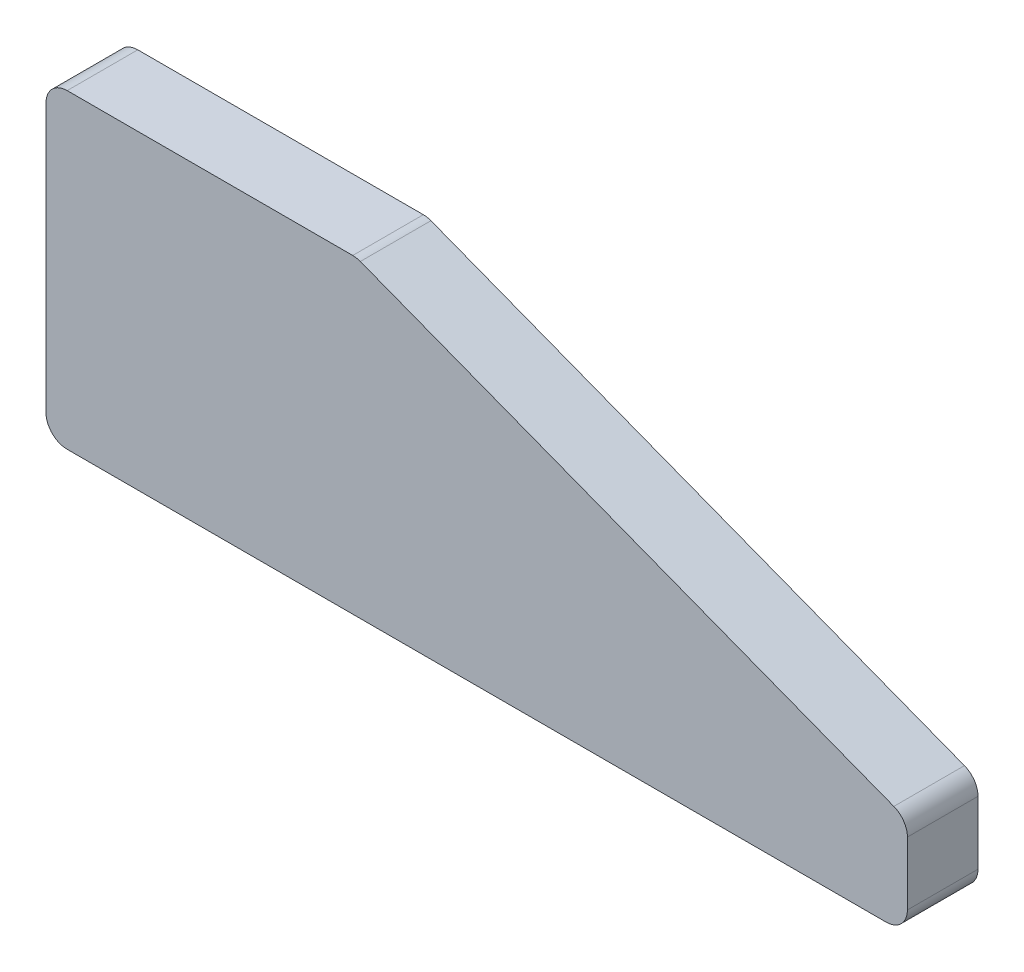
SolidWorks part; units mm, degrees
material "未指定"
ref_plane "正面" through (0, 0, 0) normal (0, 0, 1) x (1, 0, 0)
ref_plane "平面" through (0, 0, 0) normal (0, 1, 0) x (1, 0, 0)
ref_plane "右側面" through (0, 0, 0) normal (1, 0, 0) x (0, 0, -1)
sketch "ｽｹｯﾁ1" plane through (0, 0, 0) normal (0, 0, 1) x (1, 0, 0)
  line L0 (-22, -22) -> (100, -22)
  line L1 (100, -22) -> (100, -8)
  line L2 (100, -8) -> (22, 22)
  line L3 (22, 22) -> (-22, 22)
  line L4 (-22, 22) -> (-22, -22)
  line L5 (0, 0) -> (25, 0) construction
  dimension "D1" = 100
  dimension "D2" = 22
  dimension "D3" = 22
  dimension "D4" = 44
  dimension "D5" = 8
extrude "板 外形切り出し" add sketch "ｽｹｯﾁ1" along normal mid plane 10
fillet "角R" radius 3 5 edges at (-22, 22, 0) (22, 22, 0) (100, -8, 0) (100, -22, 0) (-22, -22, 0)
equation "\"JAW_LEN\" = 100"
equation "\"D1@ｽｹｯﾁ1\" = \"JAW_LEN\""
equation "\"JAW_HUB\" = 22"
equation "\"D2@ｽｹｯﾁ1\" = \"JAW_HUB\""
equation "\"D3@ｽｹｯﾁ1\" = \"JAW_HUB\""
equation "\"D4@ｽｹｯﾁ1\" = 2 * ( \"JAW_HUB\" )"
equation "\"JAW_TIP\" = 8"
equation "\"D5@ｽｹｯﾁ1\" = \"JAW_TIP\""
equation "\"PLATE_T\" = 10"
equation "\"D1@板 外形切り出し\" = \"PLATE_T\""
equation "\"JAW_R\" = 3"
equation "\"D1@角R\" = \"JAW_R\""
